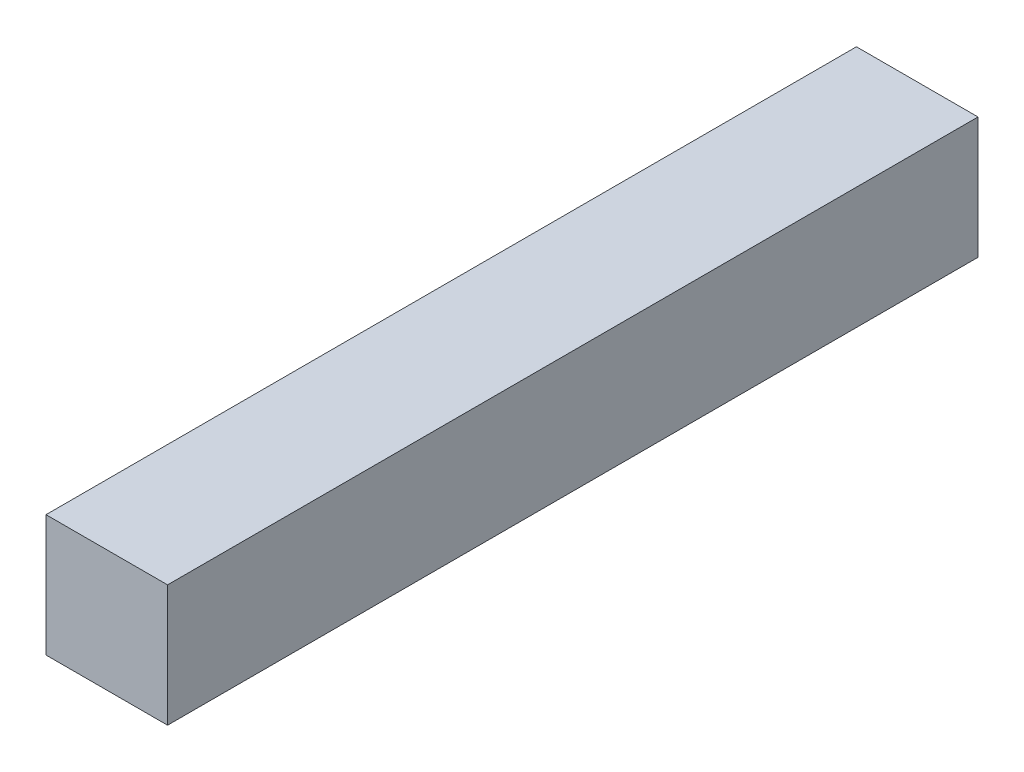
SolidWorks part; units mm, degrees
ref_plane "Front Plane" through (0, 0, 0) normal (0, 0, 1) x (1, 0, 0)
ref_plane "Top Plane" through (0, 0, 0) normal (0, 1, 0) x (1, 0, 0)
ref_plane "Right Plane" through (0, 0, 0) normal (1, 0, 0) x (0, 0, -1)
sketch "Sketch1" plane through (0, 0, 0) normal (0, 0, 1) x (1, 0, 0)
  line L1 (-3.048, 2.5763) -> (4.572, 2.5763)
  line L2 (-3.048, 2.5763) -> (-3.048, -5.0437)
  line L3 (-3.048, -5.0437) -> (4.572, -5.0437)
  line L4 (4.572, 2.5763) -> (4.572, -5.0437)
  dimension "D1" = 7.62
  dimension "D2" = 7.62
extrude "Boss-Extrude1" add sketch "Sketch1" along normal blind 50.8
